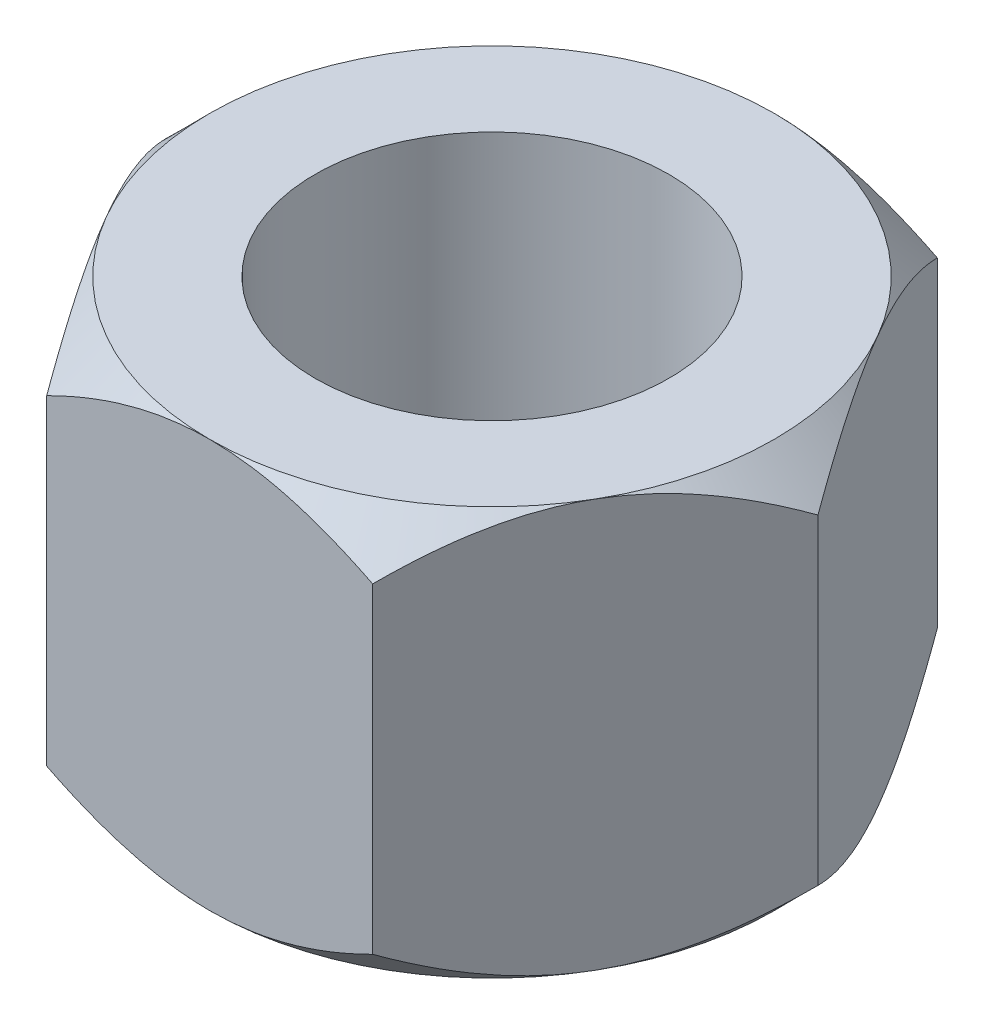
SolidWorks part; units mm, degrees
ref_plane "Front Plane" through (0, 0, 0) normal (1, 0, 0) x (0, 1, 0)
ref_plane "Top Plane" through (0, 0, 0) normal (0, 0, 1) x (0, 1, 0)
ref_plane "Right Plane" through (0, 0, 0) normal (0, 1, 0) x (-1, 0, 0)
sketch "Sketch1" plane through (0, 0, 0) normal (0, 1, 0) x (-1, 0, 0)
  line L0 (0, 0) -> (50000, 0) construction
  line L1 (47.9201, 0) -> (23.96, 41.5)
  line L2 (23.96, 41.5) -> (-23.96, 41.5)
  line L3 (-23.96, 41.5) -> (-47.9201, 0)
  line L4 (-47.9201, 0) -> (-23.96, -41.5)
  line L5 (-23.96, -41.5) -> (23.96, -41.5)
  line L6 (23.96, -41.5) -> (47.9201, 0)
  line L7 (0, 0) -> (0, 50000) construction
  circle A0 centre (0, 0) radius 41.5 construction
  dimension "D1" = 83
extrude "Boss-Extrude1" add sketch "Sketch1" along normal mid plane 60
sketch "Sketch2" plane through (0, 30, 0) normal (0, 1, 0) x (-1, 0, 0)
  circle A0 centre (0, 0) radius 26
  dimension "D1" = 52
extrude "Cut-Extrude1" cut sketch "Sketch2" against normal through all both and the other way through all
sketch "Sketch3" plane through (0, 30, 0) normal (0, 1, 0) x (-1, 0, 0)
  line L0 (-23.96, -41.5) -> (23.96, -41.5) construction
  circle A0 centre (0, 0) radius 41.5
extrude "Cut-Extrude2" cut sketch "Sketch3" against normal through all both draft 45 and the other way through all flip side to cut
mirror "Mirror1" about plane through (0, 0, 0) normal (0, 1, 0) of "Cut-Extrude2"
